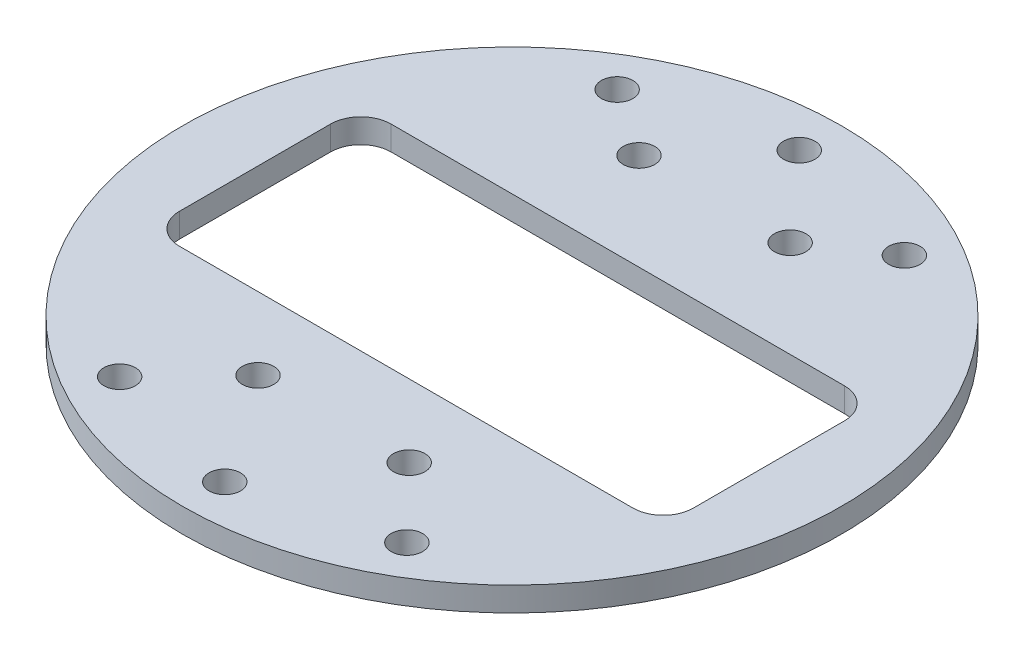
SolidWorks part; units mm, degrees
material "1060 合金"
ref_plane "前视基准面" through (0, 0, 0) normal (0, 0, 1) x (1, 0, 0)
ref_plane "上视基准面" through (0, 0, 0) normal (0, 1, 0) x (1, 0, 0)
ref_plane "右视基准面" through (0, 0, 0) normal (1, 0, 0) x (0, 0, -1)
sketch "草图1" plane through (0, 0, 0) normal (0, 1, 0) x (1, 0, 0)
  circle A0 centre (0, 0) radius 54.5
  dimension "D1" = 109
extrude "凸台-拉伸1" add sketch "草图1" along normal blind 4
sketch "草图2" plane through (0, 4, 0) normal (0, 1, 0) x (1, 0, 0)
  line L1 (-42.5, 17.5) -> (42.5, 17.5)
  line L2 (-42.5, 17.5) -> (-42.5, -17.5)
  line L3 (-42.5, -17.5) -> (42.5, -17.5)
  line L4 (42.5, 17.5) -> (42.5, -17.5)
  line L5 (-42.5, 17.5) -> (42.5, -17.5) construction
  line L6 (-42.5, -17.5) -> (42.5, 17.5) construction
  point P0 (0, 0)
  dimension "D1" = 85
  dimension "D2" = 35
extrude "切除-拉伸1" cut sketch "草图2" against normal blind 4
fillet "圆角1" radius 5 4 edges at (-42.5, 2, 17.5) (42.5, 2, -17.5) (42.5, 2, 17.5) (-42.5, 2, -17.5)
sketch "草图3" plane through (0, 0, 0) normal (0, -1, 0) x (1, 0, 0)
  line L0 (0, 0) -> (-23.75, 41.1362)
  line L1 (-23.75, 41.1362) -> (23.75, 41.1362)
  line L2 (23.75, 41.1362) -> (-0.5837, -1.011)
  circle A0 centre (0, 0) radius 47.5
  circle A2 centre (-23.75, 41.1362) radius 2.6
  circle A3 centre (23.75, 41.1362) radius 2.6
  circle A4 centre (0, 47.5) radius 2.6
  dimension "D1" = 95
  dimension "D2" = 60
  dimension "D3" = 5.2
  dimension "D4" = 5.2
  dimension "D5" = 5.2
extrude "切除-拉伸2" cut sketch "草图3" against normal blind 10 contours A0 A2 L0 | A0 A2 | L0 A2 L1 | L1 A2 A0 | A0 A4 | A0 A4 | L1 A3 L2 | L2 A3 A0 | A0 A3 L1 | A0 A3
pattern_circular "阵列(圆周)1" count 2 over 360 about axis through (0, 0, 0) along (0, 1, 0) of "切除-拉伸2"
sketch "草图4" plane through (0, 0, 0) normal (0, -1, 0) x (1, 0, 0)
  line L0 (-12.5, 29.5) -> (12.5, 29.5)
  line L1 (0, 0) -> (0, 29.5)
  line L2 (-37.5, 17.5) -> (37.5, 17.5) construction
  circle A0 centre (-12.5, 29.5) radius 2.6
  circle A1 centre (12.5, 29.5) radius 2.6
  dimension "D3" = 5.2
  dimension "D4" = 5.2
  dimension "D1" = 25
  dimension "D2" = 90
  dimension "D5" = 12
extrude "切除-拉伸3" cut sketch "草图4" against normal blind 10
sketch "草图5" plane through (0, 0, 0) normal (0, -1, 0) x (1, 0, 0)
  line L0 (0, 0) -> (0, -33.5)
  line L1 (-12.5, -33.5) -> (12.5, -33.5)
  line L2 (37.5, -17.5) -> (-37.5, -17.5) construction
  circle A0 centre (-12.5, -33.5) radius 2.6
  circle A1 centre (12.5, -33.5) radius 2.6
  point P6 (0, -33.5)
  dimension "D3" = 5.2
  dimension "D4" = 5.2
  dimension "D1" = 16
  dimension "D2" = 25
extrude "切除-拉伸4" cut sketch "草图5" against normal blind 100
